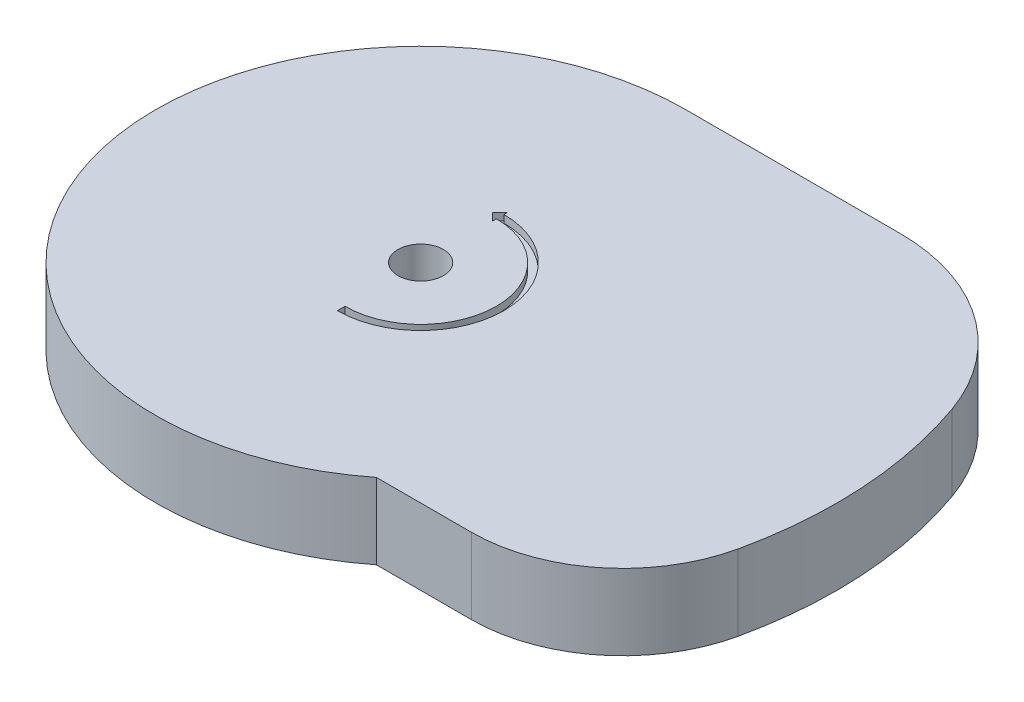
SolidWorks part; units mm, degrees
ref_plane "前基準面" through (0, 0, 0) normal (0, 0, 1) x (1, 0, 0)
ref_plane "上基準面" through (0, 0, 0) normal (0, 1, 0) x (1, 0, 0)
ref_plane "右基準面" through (0, 0, 0) normal (1, 0, 0) x (0, 0, -1)
sketch "草圖1" plane through (0, 0, 0) normal (0, 1, 0) x (1, 0, 0)
  line L0 (0, 35) -> (28.2843, 35)
  line L1 (0, -67.184) -> (0, 71.5631) construction
  line L2 (0, 0) -> (65.272, -37.6848) construction
  line L3 (34.187, -27.5) -> (21.6506, -27.5)
  line L4 (-50.4152, 0) -> (84.1624, 0) construction
  circle A0 centre (0, 0) radius 3
  arc A1 (0, 35) -> (21.6506, -27.5) centre (0, 0) ccw
  arc A2 (53.7224, -11.7857) -> (51.8545, 18.3333) centre (0, 0) ccw
  arc A3 (28.2843, 35) -> (51.8545, 18.3333) centre (28.2843, 10) cw
  arc A4 (34.187, -27.5) -> (53.7224, -11.7857) centre (34.187, -7.5) ccw
  point P14 (47.6314, -27.5)
  point P15 (55, 0)
  dimension "D1" = 70
  dimension "D2" = 110
  dimension "D3" = 6
  dimension "D5" = 25
  dimension "D7" = 20
  dimension "D8" = 55
  dimension "D4" = 120
  dimension "D6" = 30
extrude "填料-伸長1" add sketch "草圖1" along normal blind 10
sketch "草圖2" plane through (0, 10, 0) normal (0, 1, 0) x (1, 0, 0)
  line L4 (0, -10) -> (0, -11)
  line L5 (0, 11) -> (0, 10) construction
  line L7 (0, 11) -> (0, 11.5)
  line L8 (0, 11.5) -> (-1, 10.5)
  line L9 (-1, 10.5) -> (0, 9.5)
  line L10 (0, 9.5) -> (0, 10)
  line L11 (0.6189, 10.5) -> (-3.7232, 10.5) construction
  arc A0 (0, -10) -> (0, 10) centre (0, 0) ccw
  arc A1 (0, -11) -> (0, 11) centre (0, 0) ccw
  circle A2 centre (0, 0) radius 11 construction
  circle A3 centre (0, 0) radius 10 construction
  point P6 (0, 10.5)
  dimension "D1" = 20
  dimension "D2" = 1
  dimension "D3" = 1
extrude "除料-伸長1" cut sketch "草圖2" against normal blind 1
